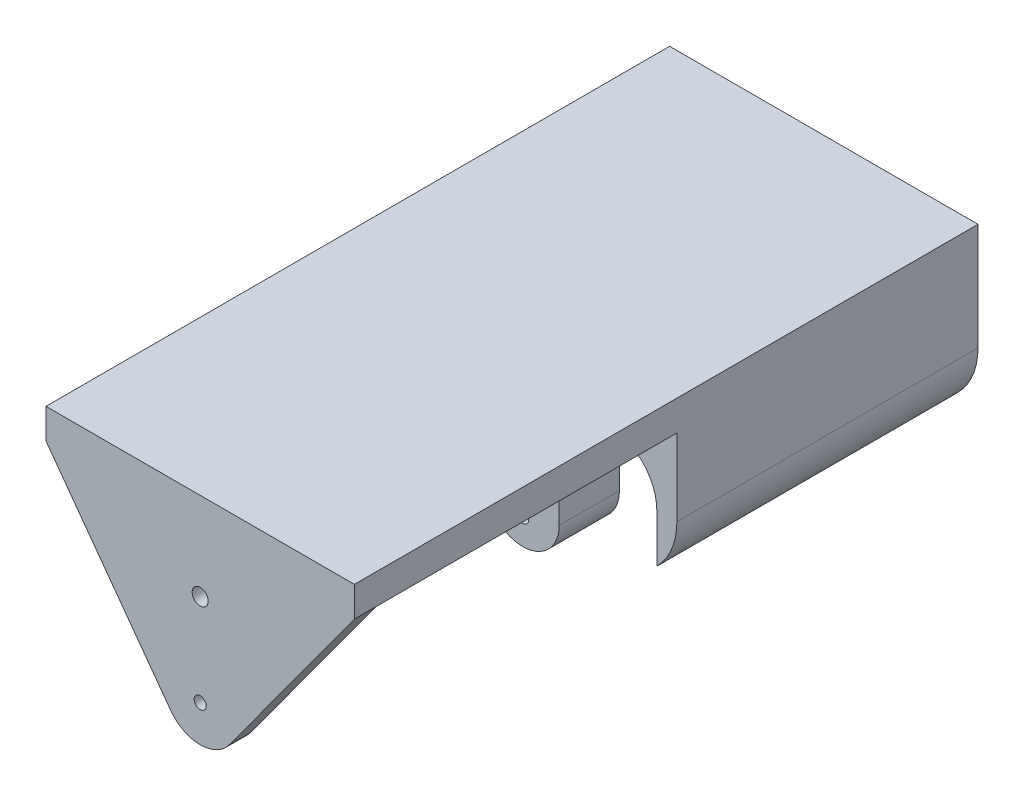
SolidWorks part; units mm, degrees
ref_plane "Płaszczyzna przednia" through (0, 0, 0) normal (0, 0, 1) x (1, 0, 0)
ref_plane "Płaszczyzna górna" through (0, 0, 0) normal (0, 1, 0) x (1, 0, 0)
ref_plane "Płaszczyzna prawa" through (0, 0, 0) normal (1, 0, 0) x (0, 0, -1)
sketch "Sketch1" plane through (0, 0, 0) normal (0, 0, 1) x (1, 0, 0)
  line L0 (-42.5, -47.31) -> (42.5, -47.31) construction
  line L1 (0, -47.31) -> (0, 0) construction
  line L2 (-42.5, -47.31) -> (42.5, -47.31) construction
  line L3 (-42.5, -13) -> (42.5, -13)
  line L4 (-42.5, -81.62) -> (42.5, -81.62)
  line L5 (-3.5724, -0.5005) -> (-51.9285, -14.3209)
  line L6 (3.5724, -0.5005) -> (51.9285, -14.3209)
  line L7 (-18.19, -47.31) -> (-18.19, -81.62)
  line L8 (-42.5, -47.31) -> (-66.81, -47.31) construction
  line L9 (-66.81, -47.31) -> (-66.81, -71.5216)
  line L10 (18.19, -47.31) -> (18.19, -81.62)
  line L12 (66.81, -47.31) -> (66.81, -71.5216)
  line L13 (0, 0) -> (-76.81, 0)
  line L14 (-76.81, 0) -> (-76.81, -47.31)
  line L15 (0, 0) -> (76.81, 0)
  line L16 (-18.19, -47.31) -> (-18.19, -4.6783)
  line L17 (18.19, -47.31) -> (18.19, -4.6783)
  line L18 (76.81, 0) -> (76.81, -47.31)
  circle A0 centre (-42.5, -47.31) radius 24.31
  circle A1 centre (42.5, -47.31) radius 24.31
  circle A4 centre (0, -13) radius 3
  arc A7 (-42.5, -13) -> (-42.5, -81.62) centre (-42.5, -47.31) ccw
  arc A8 (42.5, -81.62) -> (42.5, -13) centre (42.5, -47.31) ccw
  circle A9 centre (0, -13) radius 13
  circle A10 centre (0, -83.41) radius 3
  circle A11 centre (0, -37.71) radius 8
  arc A12 (-18.19, -78.22) -> (18.19, -78.22) centre (0, -78.22) ccw
  point P9 (0, -47.31)
  point P34 (-76.81, -47.31)
  dimension "D1" = 48.62
  dimension "D2" = 48.62
  dimension "D3" = 42.5
  dimension "D4" = 10
  dimension "6" = 6
  dimension "D5" = 10
  dimension "D6" = 6
  dimension "D7" = 36.1
  dimension "D10" = 16
  dimension "D11" = 9.6
  dimension "D8" = 85
extrude "Boss-Extrude1" add sketch "Sketch1" against normal blind 30
sketch "Sketch2" plane through (0, 0, 0) normal (0, 0, 1) x (1, 0, 0)
  circle A0 centre (42.5, -47.31) radius 24.31
sketch "Sketch3" plane through (0, 0, -30) normal (0, 0, -1) x (-1, 0, 0)
  line L0 (0, 38.22) -> (0, -81.62) construction
  line L2 (-16.5, -21.7) -> (16.5, -21.7) construction
  line L3 (16.5, -21.7) -> (16.5, -71.7) construction
  line L4 (16.5, -71.7) -> (-16.5, -71.7) construction
  line L5 (-16.5, -71.7) -> (-16.5, -21.7) construction
  line L6 (24.5, -12.8565) -> (24.5, -30.9706) construction
  line L7 (-42.5, -47.31) -> (42.5, -47.31) construction
  line L8 (-42.5, -12.8565) -> (42.5, -12.8565)
  line L9 (-42.5, -81.7635) -> (42.5, -81.7635)
  line L10 (-24.5, -12.8565) -> (-24.5, -30.9706) construction
  line L11 (-18.19, -47.31) -> (-18.19, 0)
  line L12 (-24.5, -12.8565) -> (-24.5, 0) construction
  line L13 (-24.5, 0) -> (24.5, 0)
  line L14 (24.5, 0) -> (24.5, -12.8565) construction
  line L15 (-24.5, 0) -> (-76.9535, 0)
  line L16 (-76.9535, 0) -> (-76.9535, -47.31)
  line L17 (0, 0) -> (76.9535, 0)
  line L18 (76.9535, 0) -> (76.9535, -47.31)
  line L19 (18.19, -47.31) -> (18.19, 0)
  line L20 (-66.81, -47.31) -> (-66.81, -71.7244)
  line L21 (66.81, -47.31) -> (66.81, -71.7244)
  line L22 (18.19, -19.7) -> (-18.19, -19.7)
  circle A2 centre (-42.5, -47.31) radius 24.31
  circle A3 centre (42.5, -47.31) radius 24.31
  arc A4 (-42.5, -12.8565) -> (-42.5, -81.7635) centre (-42.5, -47.31) ccw
  arc A5 (42.5, -81.7635) -> (42.5, -12.8565) centre (42.5, -47.31) ccw
  point P7 (0, -21.7)
  point P18 (0, -47.31)
  point P35 (0, 0)
  dimension "D3" = 19.7
  dimension "D4" = 48.62
  dimension "D5" = 48.62
  dimension "D6" = 34.4535
  dimension "D1" = 33
  dimension "D2" = 50
  dimension "D7" = 18
  dimension "D8" = 2
  dimension "D9" = 119.84
extrude "Boss-Extrude2" add sketch "Sketch3" along normal blind 120
sketch "Sketch4" plane through (0, 0, 0) normal (0, 0, 1) x (1, 0, 0)
sketch "Sketch5" plane through (0, 0, 0) normal (0, 0, 1) x (1, 0, 0)
  line L1 (-76.81, 0) -> (-76.81, -9)
  line L2 (-76.81, -9) -> (76.81, -9)
  line L3 (76.81, 0) -> (76.81, -47.31) construction
  line L4 (76.81, -9) -> (76.81, 0)
  line L5 (76.81, 0) -> (-76.81, 0) construction
  line L6 (76.81, 0) -> (-76.81, 0)
  line L7 (-76.81, 0) -> (-76.81, 6)
  line L8 (-76.81, 6) -> (76.81, 6)
  line L9 (76.81, 6) -> (76.81, 0)
  line M9 (76.81, -47.31) -> (76.81, 0)
  line M10 (76.81, 0) -> (-76.81, 0)
  line M11 (-76.81, 0) -> (-76.81, -47.31)
  dimension "D1" = 153.62
  dimension "D2" = 9
  dimension "D3" = 6
extrude "Boss-Extrude3" add sketch "Sketch5" along normal blind 150 contours L2 M11 M9 M10 | L9 L8 L7 M10
sketch "Sketch6" plane through (0, 0, 0) normal (0, 0, -1) x (-1, 0, 0)
  line L1 (-76.81, 6) -> (76.81, 6)
  line L2 (-76.81, 6) -> (-76.81, 0)
  line L3 (-76.81, 0) -> (76.81, 0)
  line L4 (76.81, 6) -> (76.81, 0)
  line L5 (-76.81, 6) -> (76.81, 0) construction
  line L6 (-76.81, 0) -> (76.81, 6) construction
  point P4 (0, 3)
extrude "Boss-Extrude4" add sketch "Sketch6" along normal up to surface (150 mm away) up to face at (0, -34.9722, -150)
sketch "Sketch7" plane through (0, 0, 150) normal (0, 0, 1) x (1, 0, 0)
  line L0 (-14.6943, -94.1316) -> (-76.81, -9)
  line L1 (14.6943, -94.1316) -> (76.81, -9)
  line L2 (-76.81, -9) -> (-76.81, 6)
  line L3 (-76.81, 6) -> (76.81, 6)
  line L4 (76.81, 6) -> (76.81, -9)
  line L5 (76.81, -9) -> (76.81, -47.31) construction
  circle A0 centre (0, -83.41) radius 18.19
  line M4 (-76.81, 6) -> (-76.81, -9)
  line M5 (-76.81, -9) -> (76.81, -9)
  line M6 (76.81, -9) -> (76.81, 6)
  line M7 (76.81, 6) -> (-76.81, 6)
  dimension "D1" = 36.38
extrude "Boss-Extrude5" add sketch "Sketch7" along normal blind 10.65 contours A0 L1 L0 M5 | M7 M4 M5 M6 | A0
sketch "Sketch8" plane through (0, 0, 160.65) normal (0, 0, 1) x (1, 0, 0)
  circle A0 centre (0, -83.41) radius 3 construction
  circle A1 centre (0, -83.41) radius 3 construction
  circle A2 centre (0, -37.71) radius 8 construction
  circle A3 centre (0, -37.71) radius 8 construction
  circle A4 centre (0, -83.41) radius 3
  circle A5 centre (0, -37.71) radius 4
  dimension "D1" = 6
  dimension "D2" = 8
extrude "Cut-Extrude1" cut sketch "Sketch8" against normal up to next
